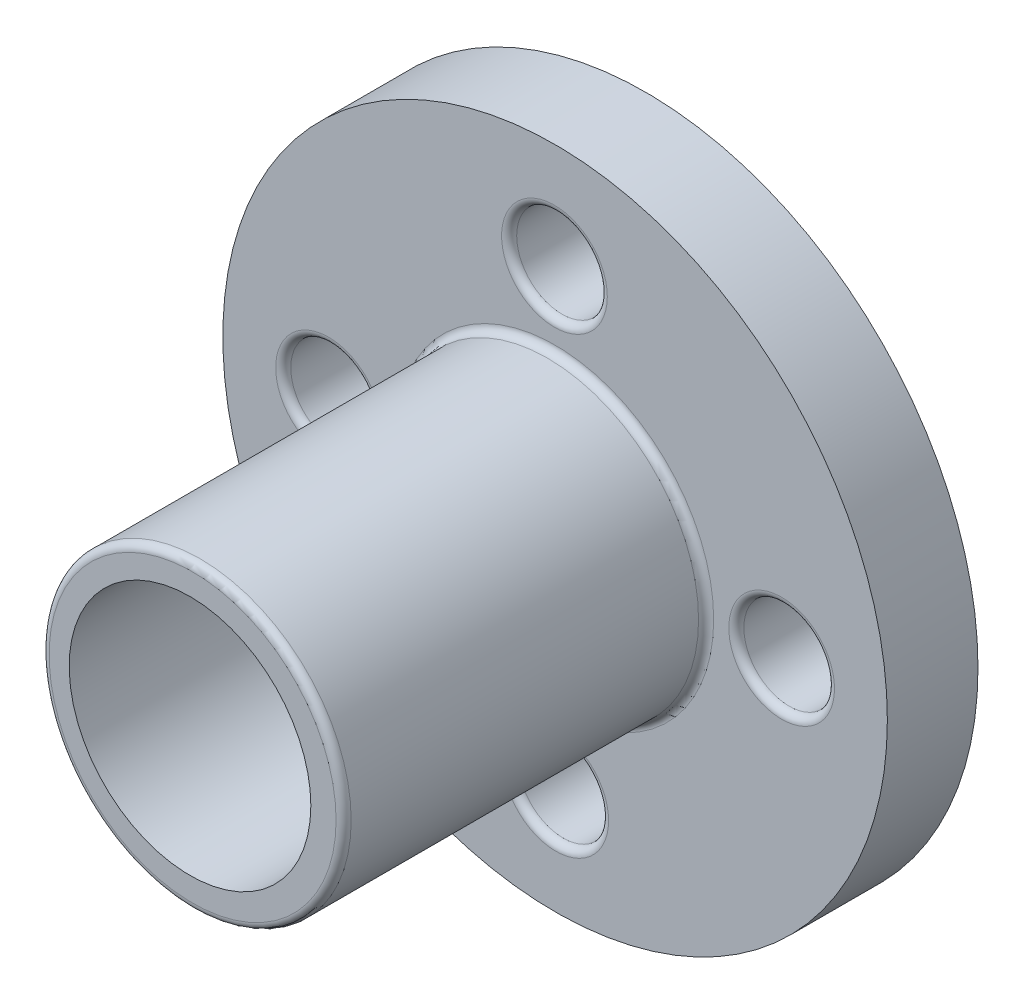
SolidWorks part; units mm, degrees
material "2.0367 (CuZn40)"
ref_plane "Plan de face" through (0, 0, 0) normal (0, 0, 1) x (1, 0, 0)
ref_plane "Plan de dessus" through (0, 0, 0) normal (0, 1, 0) x (1, 0, 0)
ref_plane "Plan de droite" through (0, 0, 0) normal (1, 0, 0) x (0, 0, -1)
sketch "Esquisse1" plane through (0, 0, 0) normal (0, 0, 1) x (1, 0, 0)
  circle A0 centre (0, 0) radius 11
  dimension "D1" = 22
extrude "Boss.-Extru.1" add sketch "Esquisse1" along normal blind 3
sketch "Esquisse2" plane through (0, 0, 3) normal (0, 0, 1) x (1, 0, 0)
  circle A0 centre (0, 0) radius 5
  circle A1 centre (-0.0858, 0) radius 4
extrude "Boss.-Extru.2" add sketch "Esquisse2" along normal blind 12
sketch "Esquisse3" plane through (0, 0, 0) normal (0, 0, -1) x (-1, 0, 0)
  circle A0 centre (0, 0) radius 4
extrude "Enlèv. mat.-Extru.1" cut sketch "Esquisse3" against normal blind 3
sketch "Esquisse4" plane through (0, 0, 0) normal (0, 0, -1) x (-1, 0, 0)
  line L0 (0.0429, 3.9998) -> (0, 11) construction
  circle A0 centre (0, 0) radius 11 construction
  circle A1 centre (0.0214, 7.4999) radius 1.5
  circle A2 centre (7.4999, -0.0214) radius 1.5
  circle A3 centre (-0.0214, -7.4999) radius 1.5
  circle A4 centre (-7.4999, 0.0214) radius 1.5
  point P15 (0, 0)
  dimension "D1" = 4
extrude "Enlèv. mat.-Extru.2" cut sketch "Esquisse4" against normal blind 12
fillet "Congé1" radius 0.25 4 edges at (-5.9999, -0.0214, 3) (1.5214, -7.4999, 3) (8.9999, 0.0214, 3) (1.4786, 7.4999, 3)
fillet "Congé2" radius 0.25 1 edges at (5, 0, 15)
fillet "Congé3" radius 0.25 1 edges at (5, 0, 3)
